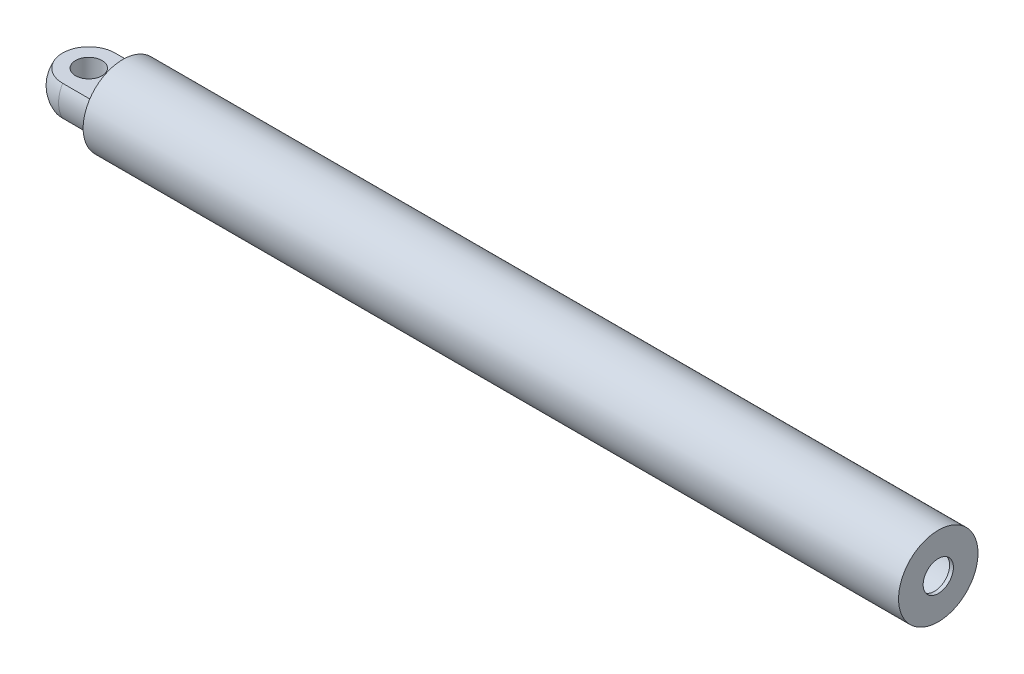
SolidWorks part; units mm, degrees
material "Q235"
ref_plane "前视基准面" through (0, 0, 0) normal (0, 0, 1) x (1, 0, 0)
ref_plane "上视基准面" through (0, 0, 0) normal (0, 1, 0) x (1, 0, 0)
ref_plane "右视基准面" through (0, 0, 0) normal (1, 0, 0) x (0, 0, -1)
sketch "草图1" plane through (0, 0, 0) normal (0, 0, 1) x (1, 0, 0)
  line L0 (0, 0) -> (35, 0) construction
  line L1 (35, -40) -> (35, 40)
  line L2 (35, 40) -> (69.282, 40)
  line L3 (35, -40) -> (69.282, -40)
  line L4 (0, 0) -> (0, 40.8031) construction
  arc A1 (69.282, -40) -> (69.282, 40) centre (0, 0) ccw
  point P6 (35, 0)
  dimension "D1" = 80
  dimension "D3" = 160
  dimension "D2" = 35
revolve "旋转1" add sketch "草图1" angle 360 about L4
sketch "草图3" plane through (0, 40, 0) normal (0, 1, 0) x (1, 0, 0)
  line L1 (88.4798, 86.3069) -> (0, 86.3069)
  line L2 (88.4798, 86.3069) -> (88.4798, -69.7658)
  line L3 (88.4798, -69.7658) -> (0, -69.7658)
  line L4 (0, 86.3069) -> (0, -69.7658)
extrude "切除-拉伸1" cut sketch "草图3" against normal blind 112
sketch "草图4" plane through (0, 0, 0) normal (1, 0, 0) x (0, 0, -1)
  line L0 (-69.282, 40) -> (69.282, 40)
  line L1 (-69.282, -40) -> (69.282, -40)
  arc A0 (-69.282, 40) -> (-69.282, -40) centre (0, 0) ccw
  arc A1 (69.282, -40) -> (69.282, 40) centre (0, 0) ccw
extrude "凸台-拉伸3" add sketch "草图4" along normal blind 90
sketch "草图5" plane through (0, 40, 0) normal (0, 1, 0) x (1, 0, 0)
  circle A0 centre (0, 0) radius 35
extrude "切除-拉伸2" cut sketch "草图5" against normal through all
sketch "草图6" plane through (90, 0, 0) normal (1, 0, 0) x (0, 0, -1)
  circle A0 centre (0, 0) radius 105
  dimension "D1" = 210
extrude "凸台-拉伸4" add sketch "草图6" along normal blind 25
sketch "草图7" plane through (115, 0, 0) normal (1, 0, 0) x (0, 0, -1)
  circle A0 centre (0, 0) radius 105
  circle A1 centre (0, 0) radius 90
  dimension "D1" = 180
  dimension "D2" = 210
extrude "凸台-拉伸5" add sketch "草图7" along normal blind 2130
sketch "草图8" plane through (2245, 0, 0) normal (1, 0, 0) x (0, 0, -1)
  circle A0 centre (0, 0) radius 90
  circle A1 centre (0, 0) radius 40
  dimension "D1" = 180
  dimension "D2" = 80
extrude "凸台-拉伸6" add sketch "草图8" against normal blind 10
ref_plane "基准面2" through (0, 0, -90) normal (0, 0, -1) x (-1, 0, 0)
sketch "草图9" plane through (0, 0, -90) normal (0, 0, -1) x (-1, 0, 0)
  line L0 (0, 0) -> (-2245, 0) construction
  line L1 (-2245, 105) -> (-2245, -105) construction
  circle A0 centre (-2150, 0) radius 13.5
  circle A1 centre (-125, 0) radius 13.5
  dimension "D1" = 27
  dimension "D2" = 95
  dimension "D3" = 125
  dimension "D4" = 27
extrude "凸台-拉伸7" add sketch "草图9" along normal blind 31 separate body
sketch "草图10" plane through (0, 0, -90) normal (0, 0, -1) x (-1, 0, 0)
  line L0 (0, 0) -> (-257.5, 0) construction
  line L2 (-295, -15) -> (-220, -15)
  line L3 (-295, -15) -> (-295, 15)
  line L4 (-295, 15) -> (-220, 15)
  line L5 (-220, -15) -> (-220, 15)
  line L6 (-295, -15) -> (-220, 15) construction
  line L7 (-295, 15) -> (-220, -15) construction
  dimension "D1" = 220
  dimension "D2" = 75
  dimension "D3" = 30
extrude "凸台-拉伸8" add sketch "草图10" along normal blind 40 separate body
ref_plane "基准面3" through (2150, 0, 0) normal (1, 0, 0) x (0, 0, -1)
sketch "草图11" plane through (2150, 0, 0) normal (1, 0, 0) x (0, 0, -1)
  line L0 (0, 0) -> (110, 0) construction
  circle A0 centre (110, 0) radius 8
  circle A1 centre (110, 0) radius 5.5
  dimension "D1" = 16
  dimension "D2" = 2.5
  dimension "D3" = 110
extrude "凸台-拉伸9" add sketch "草图11" against normal up to surface (1855 mm away) up to face at (295, 0, -110)
ref_plane "基准面4" through (125, 0, 0) normal (1, 0, 0) x (0, 0, -1)
sketch "草图12" plane through (125, 0, 0) normal (1, 0, 0) x (0, 0, -1)
  line L0 (0, 0) -> (110, 0) construction
  circle A0 centre (110, 0) radius 8
  circle A1 centre (110, 0) radius 5.5
  dimension "D2" = 2.5
  dimension "D3" = 16
  dimension "D1" = 110
extrude "凸台-拉伸10" add sketch "草图12" along normal up to surface (95 mm away) up to face at (220, 0, -110)
hole_wizard "M18x1.5 螺纹孔1" positions "草图13" profile "草图14" tap size "M18x1.5" standard "GB"
sketch "草图13" plane through (0, 0, -130) normal (0, 0, -1) x (-1, 0, 0)
  line L0 (-295, 0) -> (-220, 0) construction
  line L1 (-295, 15) -> (-295, -15) construction
  line L2 (-220, -15) -> (-220, 15) construction
  point P0 (-277.5, 0)
  point P2 (-237.5, 0)
  dimension "D1" = 40
  dimension "D2" = 17.5
sketch "草图14" plane through (277.5, 0, -130) normal (1, 0, 0) x (0, 1, 0)
  line L0 (0, 0) -> (0, 39.9571)
  line L1 (0, 39.9571) -> (8.25, 35)
  line L2 (8.25, 35) -> (8.25, 0)
  line L5 (8.25, 0) -> (0, 0)
  line L10 (0, 39.9571) -> (-8.25, 35) construction
  line L11 (0, -6.35) -> (0, 107.95) construction
  dimension "螺纹孔钻头直径" = 16.5
  dimension "螺纹孔钻头深度" = 35
  dimension "导头角度" = 118
cosmetic thread "孔螺蚊线1" parameters "D1"=30, "D2"=18
cosmetic thread "孔螺蚊线2" parameters "D1"=30, "D2"=18
